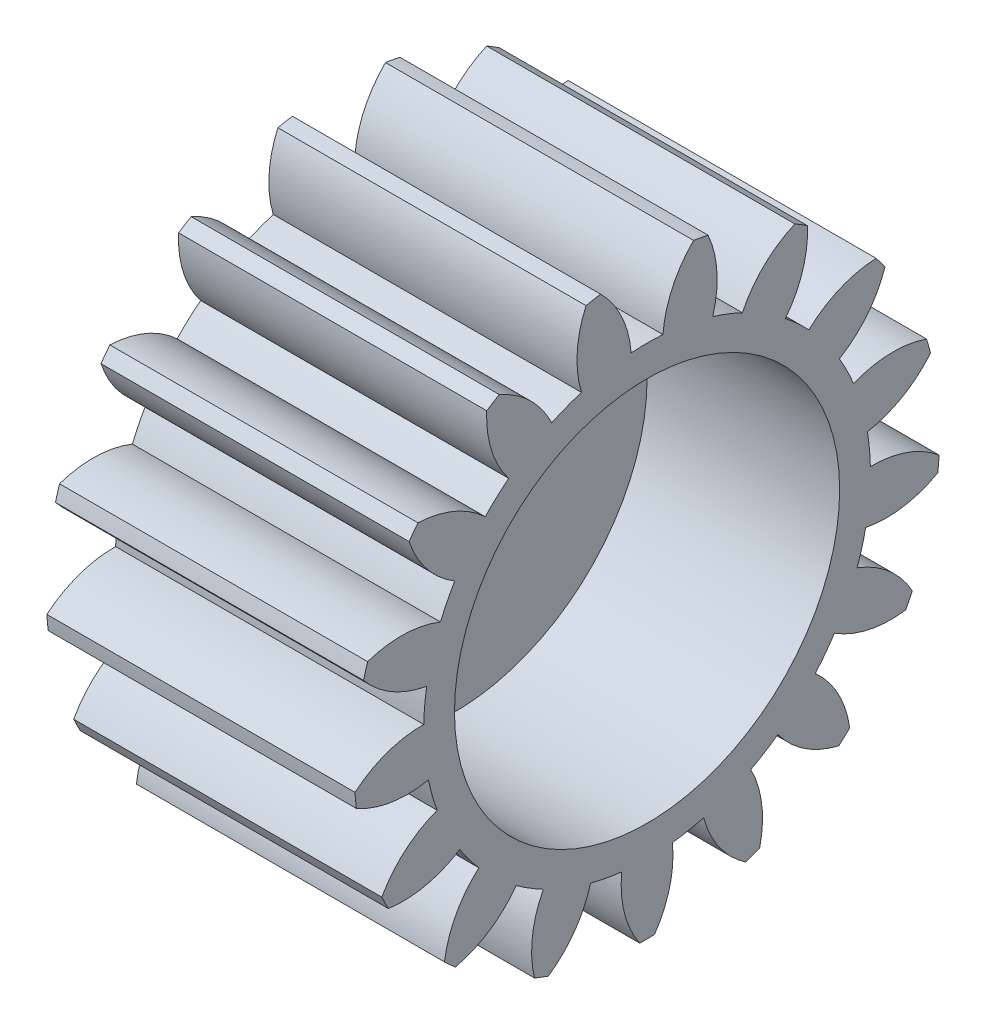
SolidWorks part; units mm, degrees
ref_plane "Plane1" through (0, 0, 0) normal (0, 0, 1) x (1, 0, 0)
ref_plane "Plane2" through (0, 0, 0) normal (0, 1, 0) x (1, 0, 0)
ref_plane "Plane3" through (0, 0, 0) normal (1, 0, 0) x (0, 0, -1)
other "Configuration Table"
sketch "HoldingSke" plane through (0, 0, 0) normal (0, 1, 0) x (1, 0, 0)
  line L0 (0, 0) -> (1.1954, -0.3655)
  line L1 (-15, 0) -> (100, 0) construction
  line L2 (0, 0) -> (-2.1039, 2.3779)
  line L3 (0, 0) -> (-11.863, 4.5341)
  line L4 (0, 0) -> (8.2586, 2.5249)
  line L5 (0, 0) -> (-46.8476, -17.4728)
  line L6 (0, 0) -> (-6.6317, -4.4744)
  line L7 (-2.1039, 2.3779) -> (8.6586, 51.2059)
  line L8 (-76.2, 54.61) -> (-74.4, 54.61)
  line L9 (-71.009, 38.7566) -> (-53.1078, 45.2721)
  line L10 (-76.2, 71.12) -> (104.1128, 71.12)
  line L11 (0, 0) -> (-8, 0)
  line L12 (-76.2, 101.6) -> (-76.17, 101.6)
  line L13 (24.9733, 27.94) -> (52.9518, 28.4284)
  line L14 (24.9733, 27.94) -> (24.9743, 27.94)
  line L15 (24.9733, 27.94) -> (100.4006, 29.5858)
  line L16 (-63.627, -0.8) -> (-12.827, -0.8)
  circle A0 centre (0, 0) radius 5
  circle A1 centre (0, 0) radius 5.799
  circle A2 centre (0, 0) radius 37.5
  circle A3 centre (0, 0) radius 5
  dimension "MHD" = 11.598
  dimension "Hub_dia" = 75
  dimension "Bore" = 10
  dimension "MBD" = 10
  dimension "Num_teeth" = 17
  dimension "Pitch" = 1.25
  dimension "Overall_len" = 50
  dimension "Show_teeth" = 17
  dimension "Thickness" = 8
  dimension "OAL" = 50.0001
  dimension "T_dim" = 1.8
  dimension "Ap" = 20
  dimension "H" = 19.05
  dimension "Pitch_radius" = 180.3128
  dimension "Width" = 8
  dimension "Backlash" = 0.03
  dimension "Addendum_fac" = 1
  dimension "Dedendum_fac" = 1.25
  dimension "Clearance_fac" = 0.25
  dimension "Dedendum_add" = 0.001
  dimension "Module" = 0.8
sketch "BasProSke" plane through (0, 0, 0) normal (0, 1, 0) x (1, 0, 0)
  line L0 (-10, 0) -> (60, 0) construction
  line L1 (0, 0) -> (0, 7.6)
  line L2 (0, 0) -> (8, 0)
  line L3 (8, 0) -> (8, 7.6)
  line L4 (8, 7.6) -> (0, 7.6)
  dimension "Thickness" = 8
  dimension "Diameter" = 15.2
revolve "Base-Revolve" add sketch "BasProSke" angle 360 about L0
sketch "TooCutSke" plane through (0, 0, 0) normal (1, 0, 0) x (0, 0, -1)
  line L1 (0, 0) -> (0, 107) construction
  line L2 (0, 0) -> (-0.6799, 6.7659) construction
  line L3 (0, 0) -> (-2.49, 13.3206) construction
  line L4 (-0.6799, 6.7659) -> (-1.245, 6.6603) construction
  arc A0 (0.4129, 5.7843) -> (-0.4129, 5.7843) centre (0, 0) ccw
  arc A1 (1.2302, 7.5255) -> (-1.2302, 7.5255) centre (0, 0) ccw
  circle A2 centre (0, 0) radius 6.8 construction
  circle A3 centre (0, 0) radius 6.3899 construction
  arc A4 (-0.4129, 5.7843) -> (-1.2302, 7.5255) centre (-3.1247, 5.5738) ccw
  arc A5 (1.2302, 7.5255) -> (0.4129, 5.7843) centre (3.1247, 5.5738) ccw
  dimension "Root_dia" = 11.598
  dimension "Overcut_dia" = 15.2508
  dimension "Pitch_dia" = 13.6
  dimension "Base_dia" = 12.7798
  dimension "Flank_rad" = 2.72
  dimension "Half_ang" = 10.588
  dimension "Half_CT" = 0.5749
extrude "ToothCut" cut sketch "TooCutSke" along normal through all
fillet "Breaks" [suppressed] radius 0.016
fillet "RootFillets" [suppressed] radius 0.201
pattern_circular "TeethCuts" count 17 every 21.176 about axis through (-10, 0, 0) along (1, 0, 0) of "ToothCut", "RootFillets", "Breaks"
sketch "HubNeaOneSke" plane through (0, 0, 0) normal (-1, 0, 0) x (0, 0, 1)
  circle A0 centre (0, 0) radius 5.799
  dimension "Diameter" = 11.598
extrude "HubNearOne" [suppressed] add sketch "HubNeaOneSke" along normal blind 42.0001
sketch "HubNeaBotSke" plane through (0, 0, 0) normal (-1, 0, 0) x (0, 0, 1)
  circle A0 centre (0, 0) radius 5.799
  dimension "Diameter" = 11.598
extrude "HubNearBoth" [suppressed] add sketch "HubNeaBotSke" along normal blind 21
ref_plane "FarPln" through (8, 0, 0) normal (1, 0, 0) x (0, 0, -1)
sketch "HubFarSke" plane through (8, 0, 0) normal (1, 0, 0) x (0, 0, -1)
  circle A0 centre (0, 0) radius 5.799
  dimension "Diameter" = 11.598
extrude "HubFar" [suppressed] add sketch "HubFarSke" along normal blind 21
sketch "BorSke" plane through (0, 0, 0) normal (1, 0, 0) x (0, 0, -1)
  circle A0 centre (0, 0) radius 5
  dimension "Diameter" = 10
extrude "Bore" cut sketch "BorSke" along normal mid plane 100.0001
sketch "KeySke" plane through (0, 0, 0) normal (1, 0, 0) x (0, 0, -1)
  line L0 (-2, 0) -> (-2, 6.8)
  line L1 (-2, 6.8) -> (2, 6.8)
  line L2 (2, 6.8) -> (2, 0)
  line L3 (0, 0) -> (0, 34) construction
  line L4 (-2, 0) -> (2, 0)
  dimension "Offset" = 6.8
  dimension "Width" = 4
extrude "Keyway" [suppressed] cut sketch "KeySke" along normal mid plane 100.0001
pattern_circular "Keyway2" [suppressed] count 2 every 90 about axis through (-10, 0, 0) along (1, 0, 0)
sketch "Sketch1" plane through (0, 0, 0) normal (-1, 0, 0) x (0, 0, 1)
  circle A0 centre (0, 0) radius 5
extrude "Boss-Extrude1" add sketch "Sketch1" against normal blind 3
equation "' \"Module@HoldingSke\" = 6.35"
equation "' \"Num_teeth@HoldingSke\" = 12"
equation "' \"Ap@HoldingSke\" =  20"
equation "' \"Ap@HoldingSke\" = 20"
equation "' \"Width@HoldingSke\" = 0.5 * 25.4"
equation "' \"Hub_dia@HoldingSke\"= 1 * 25.4"
equation "' \"Hub_dia@HoldingSke\" = 1 * 25.4"
equation "' \"Overall_len@HoldingSke\" = 1.0 * 25.4"
equation "' \"Bore@HoldingSke\" = 0.75 * 25.4"
equation "' \"T_dim@HoldingSke\" = 0.1 * 25.4"
equation "' \"Width@KeySke\" = 0.25 * 25.4"
equation "' \"Show_teeth@HoldingSke\" = 13"
equation "' \"Backlash@HoldingSke\" = 0.009 * 25.4"
equation "' \"Addendum_fac@HoldingSke\" = 1.0"
equation "' \"Dedendum_fac@HoldingSke\" = 1.25"
equation "' \"Dedendum_add@HoldingSke\" = 0.00005 * 25.4"
equation "' \"Clearance_fac@HoldingSke\" = 0.25"
equation "\"Pitch@HoldingSke\" = 1 / \"Module@HoldingSke\""
equation "\"Overcut_dia@TooCutSke\" = (\"Num_teeth@HoldingSke\" + 2 * \"Addendum_fac@HoldingSke\") / \"Pitch@HoldingSke\" + 0.002 * 25.4"
equation "\"Pitch_dia@TooCutSke\" = \"Num_teeth@HoldingSke\" / \"Pitch@HoldingSke\""
equation "\"Base_dia@TooCutSke\" = \"Num_teeth@HoldingSke\" / \"Pitch@HoldingSke\" * cos((\"Ap@HoldingSke\"  * 3.14159265 / 180))"
equation "\"Root_dia@TooCutSke\" = (\"Num_teeth@HoldingSke\" + 2) / \"Pitch@HoldingSke\" - 2 * (\"Addendum_fac@HoldingSke\" + \"Dedendum_fac@HoldingSke\") / \"Pitch@HoldingSke\" - \"Dedendum_add@HoldingSke\" * 2"
equation "\"Half_ang@TooCutSke\" = 180 / \"Num_teeth@HoldingSke\""
equation "\"Half_CT@TooCutSke\" = \"Num_teeth@HoldingSke\" / \"Pitch@HoldingSke\" * sin((3.14159265 / 2 / \"Num_teeth@HoldingSke\")) / 2 - 7 * \"Backlash@HoldingSke\" / 4"
equation "\"Flank_rad@TooCutSke\" = \"Num_teeth@HoldingSke\" / \"Pitch@HoldingSke\" / 5"
equation "\"Radius@RootFillets\" = \"Clearance_fac@HoldingSke\" / \"Pitch@HoldingSke\" + \"Dedendum_add@HoldingSke\""
equation "\"Break_rad@Breaks\" = 0.02 / \"Pitch@HoldingSke\""
equation "\"Thickness@HoldingSke\" = \"Width@HoldingSke\""
equation "\"OAL@HoldingSke\" = \"Thickness@HoldingSke\""
equation "\"MHD@HoldingSke\" = (\"Num_teeth@HoldingSke\" + 2) / \"Pitch@HoldingSke\" - 2 * (\"Addendum_fac@HoldingSke\" + \"Dedendum_fac@HoldingSke\")  / \"Pitch@HoldingSke\" - \"Dedendum_add@HoldingSke\" * 2"
equation "\"MBD@HoldingSke\" = (\"Num_teeth@HoldingSke\" + 2) / \"Pitch@HoldingSke\" - 2 * (\"Addendum_fac@HoldingSke\" + \"Dedendum_fac@HoldingSke\")  / \"Pitch@HoldingSke\" - \"Dedendum_add@HoldingSke\" * 2 - 0.002 * 25.4"
equation "\"MHD@HoldingSke\" = ((sgn( \"MHD@HoldingSke\" - \"Hub_dia@HoldingSke\" )-1)*( \"MHD@HoldingSke\" - \"Hub_dia@HoldingSke\" ))/-2+ \"Hub_dia@HoldingSke\""
equation "\"MBD@HoldingSke\" = ((sgn( \"MBD@HoldingSke\" - \"Bore@HoldingSke\" )-1)*( \"MBD@HoldingSke\" - \"Bore@HoldingSke\" ))/-2+ \"Bore@HoldingSke\""
equation "\"OAL@HoldingSke\" = ((sgn( \"OAL@HoldingSke\" - \"Overall_len@HoldingSke\" )+1)*( \"OAL@HoldingSke\" - \"Overall_len@HoldingSke\" ))/2 + \"Overall_len@HoldingSke\" + 0.000002 * 25.4"
equation "\"Num_teeth@TeethCuts\" = int( \"Show_teeth@HoldingSke\" ) + 1"
equation "\"Num_teeth@TeethCuts\" = ((sgn( \"Num_teeth@TeethCuts\" - \"Num_teeth@HoldingSke\" )-1)*( \"Num_teeth@TeethCuts\" - \"Num_teeth@HoldingSke\" ))/-2+ \"Num_teeth@HoldingSke\""
equation "\"Num_teeth@TeethCuts\" = ((sgn( \"Num_teeth@TeethCuts\" - 2.0)+1)*( \"Num_teeth@TeethCuts\" - 2.0))/2 +2.0"
equation "\"Angle@TeethCuts\" = 360.0 / \"Num_teeth@HoldingSke\""
equation "\"Diameter@BasProSke\" = (\"Num_teeth@HoldingSke\" + 2 * \"Addendum_fac@HoldingSke\") / \"Pitch@HoldingSke\""
equation "\"Thickness@BasProSke\"  = \"Thickness@HoldingSke\""
equation "' \"Fillet_rad@BasProSke\" =  \"Thickness@HoldingSke\" * 0.05"
equation "' \"Fillet_rad@BasProSke\" = \"Thickness@HoldingSke\" * 0.05"
equation "\"MHD@HoldingSke\" = ((sgn( \"MHD@HoldingSke\" - \"Root_dia@TooCutSke\" )-1)*( \"MHD@HoldingSke\" - \"Root_dia@TooCutSke\" ))/-2+ \"Root_dia@TooCutSke\""
equation "\"Diameter@HubNeaOneSke\" = \"MHD@HoldingSke\""
equation "\"Length@HubNearOne\" = \"OAL@HoldingSke\" - \"Thickness@BasProSke\""
equation "\"Diameter@HubNeaBotSke\" = \"MHD@HoldingSke\""
equation "\"Length@HubNearBoth\" = ( \"OAL@HoldingSke\" - \"Thickness@BasProSke\" ) / 2.0"
equation "\"Thickness@FarPln\" = \"Thickness@BasProSke\""
equation "\"Diameter@HubFarSke\" = \"MHD@HoldingSke\""
equation "\"Length@HubFar\" = ( \"OAL@HoldingSke\" - \"Thickness@BasProSke\" ) / 2.0"
equation "\"Diameter@BorSke\" = \"MBD@HoldingSke\""
equation "\"D1@Bore\" = \"OAL@HoldingSke\" * 2.0"
equation "\"D1@Keyway\" = \"OAL@HoldingSke\" * 2.0"
equation "\"Offset@KeySke\" = \"T_dim@HoldingSke\" + \"MBD@HoldingSke\" / 2.0"
